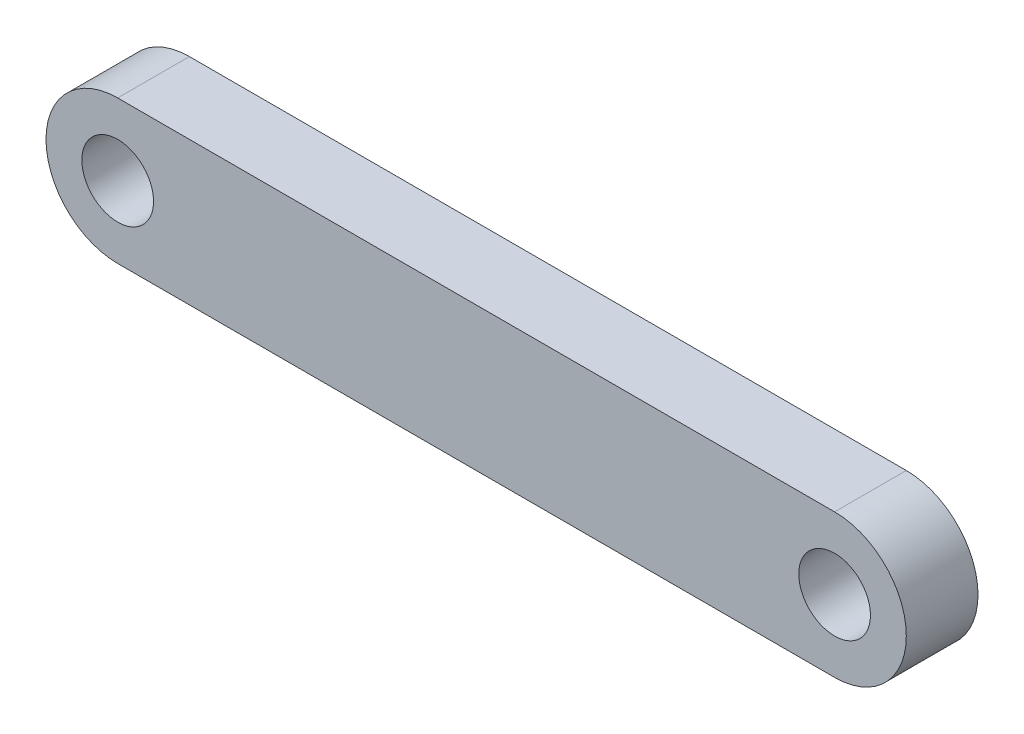
SolidWorks part; units mm, degrees
material "AISI 1035 Steel (SS)"
ref_plane "Front Plane" through (0, 0, 0) normal (0, 0, 1) x (1, 0, 0)
ref_plane "Top Plane" through (0, 0, 0) normal (0, 1, 0) x (1, 0, 0)
ref_plane "Right Plane" through (0, 0, 0) normal (1, 0, 0) x (0, 0, -1)
sketch "Sketch1" plane through (0, 0, 0) normal (0, 0, 1) x (1, 0, 0)
  line L0 (-50, 0) -> (50, 0) construction
  line L1 (-50, 10) -> (50, 10)
  line L2 (-50, -10) -> (50, -10)
  line L3 (0, 55.6084) -> (0, -51.9962) construction
  arc A0 (-50, 10) -> (-50, -10) centre (-50, 0) ccw
  arc A1 (50, -10) -> (50, 10) centre (50, 0) ccw
  circle A2 centre (50, 0) radius 5
  circle A3 centre (-50, 0) radius 5
  point P2 (0, 0)
  dimension "D3" = 10
  dimension "D1" = 50
  dimension "D2" = 20
extrude "Boss-Extrude1" add sketch "Sketch1" along normal blind 10
